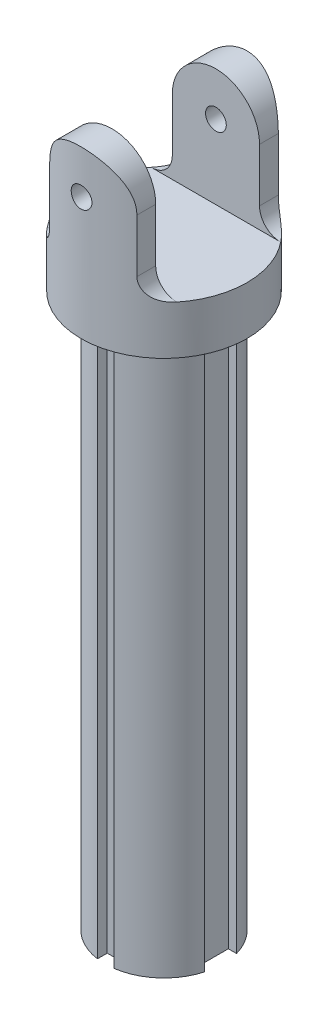
SolidWorks part; units mm, degrees
ref_plane "Front Plane" through (0, 0, 0) normal (0, 0, 1) x (1, 0, 0)
ref_plane "Top Plane" through (0, 0, 0) normal (0, 1, 0) x (1, 0, 0)
ref_plane "Right Plane" through (0, 0, 0) normal (1, 0, 0) x (0, 0, -1)
sketch "Sketch1" plane through (0, 0, 0) normal (0, 1, 0) x (1, 0, 0)
  circle A0 centre (0, 0) radius 6
  point P2 (0, 0)
  dimension "D1" = 12
extrude "Boss-Extrude1" add sketch "Sketch1" along normal blind 12
sketch "Sketch2" plane through (0, 0, 0) normal (1, 0, 0) x (0, 0, -1)
  line L0 (6, 12) -> (-6, 12) construction
  line L1 (-3.75, 12) -> (3.75, 12)
  line L2 (-3.75, 12) -> (-3.75, 3.5)
  line L3 (-3.75, 3.5) -> (3.75, 3.5)
  line L4 (3.75, 12) -> (3.75, 3.5)
  line L5 (-6, 0) -> (6, 0) construction
  point P8 (0, 3.5)
  point P9 (0, 0)
  dimension "D1" = 3.5
  dimension "D2" = 7.5
extrude "Cut-Extrude1" cut sketch "Sketch2" against normal through all both and the other way through all contours L2 L1 L4 L3
sketch "Sketch3" plane through (0, 0, 0) normal (0, 0, 1) x (1, 0, 0)
  line L0 (4.6837, 12) -> (-4.6837, 12) construction
  line L1 (-3.15, 8.85) -> (-3.15, 5)
  line L2 (-4.65, 3.5) -> (-4.6837, 3.5)
  line L3 (-4.6837, 12) -> (-4.6837, 3.5) construction
  line L4 (4.6837, 12) -> (-4.6837, 12)
  line L5 (-4.6837, 12) -> (-4.6837, 3.5)
  line L7 (0, -6.6) -> (0, 6.6) construction
  line L8 (4.6837, 12) -> (4.6837, 3.5)
  line L9 (4.65, 3.5) -> (4.6837, 3.5)
  line L10 (3.15, 8.85) -> (3.15, 5)
  arc A0 (3.15, 8.85) -> (-3.15, 8.85) centre (0, 8.85) ccw
  arc A1 (-3.15, 5) -> (-4.65, 3.5) centre (-4.65, 5) cw
  arc A2 (3.15, 5) -> (4.65, 3.5) centre (4.65, 5) ccw
  circle A3 centre (0, 8.85) radius 0.75
  dimension "D1" = 6.3
  dimension "D2" = 1.5
  dimension "D3" = 1.5
extrude "Cut-Extrude2" cut sketch "Sketch3" against normal through all both and the other way through all contours A1 L1 A0 L4 L5 L2 | L10 A2 L9 L8 L4 A0 | A3
sketch "Sketch4" plane through (0, 0, 0) normal (0, -1, 0) x (1, 0, 0)
  line L1 (-0.6, 5) -> (0.6, 5)
  line L2 (-0.6, 5) -> (-0.6, 3.5)
  line L3 (-0.6, 3.5) -> (0.6, 3.5)
  line L4 (0.6, 5) -> (0.6, 3.5)
  line L5 (-0.6, 5) -> (0.6, 3.5) construction
  line L6 (-0.6, 3.5) -> (0.6, 5) construction
  line L7 (5, 1.15) -> (3.5, 1.15)
  line L8 (5, 1.15) -> (5, -1.15)
  line L9 (5, -1.15) -> (3.5, -1.15)
  line L10 (3.5, 1.15) -> (3.5, -1.15)
  line L11 (5, 1.15) -> (3.5, -1.15) construction
  line L12 (5, -1.15) -> (3.5, 1.15) construction
  line L13 (-5, -1.15) -> (-3.5, -1.15)
  line L14 (-5, -1.15) -> (-5, 1.15)
  line L15 (-5, 1.15) -> (-3.5, 1.15)
  line L16 (-3.5, -1.15) -> (-3.5, 1.15)
  line L17 (-5, -1.15) -> (-3.5, 1.15) construction
  line L18 (-5, 1.15) -> (-3.5, -1.15) construction
  line L19 (-0.6, -5) -> (0.6, -5)
  line L20 (-0.6, -5) -> (-0.6, -3.5)
  line L21 (-0.6, -3.5) -> (0.6, -3.5)
  line L22 (0.6, -5) -> (0.6, -3.5)
  line L23 (-0.6, -5) -> (0.6, -3.5) construction
  line L24 (-0.6, -3.5) -> (0.6, -5) construction
  circle A0 centre (0, 0) radius 4.25
  point P3 (0, 4.25)
  point P8 (4.25, 0)
  point P13 (-4.25, 0)
  point P18 (0, -4.25)
  point P23 (0, 4.2186)
  point P24 (3.2207, 0.9086)
  point P25 (-0.6276, -3.5229)
  dimension "D4" = 8.5
  dimension "D1" = 2.3
  dimension "D2" = 1.2
  dimension "D3" = 1.5
extrude "Boss-Extrude2" add sketch "Sketch4" along normal blind 40 contours L22 A0 L9 L10 L7 L4 L3 L2 L15 L16 L13 L20 L21
